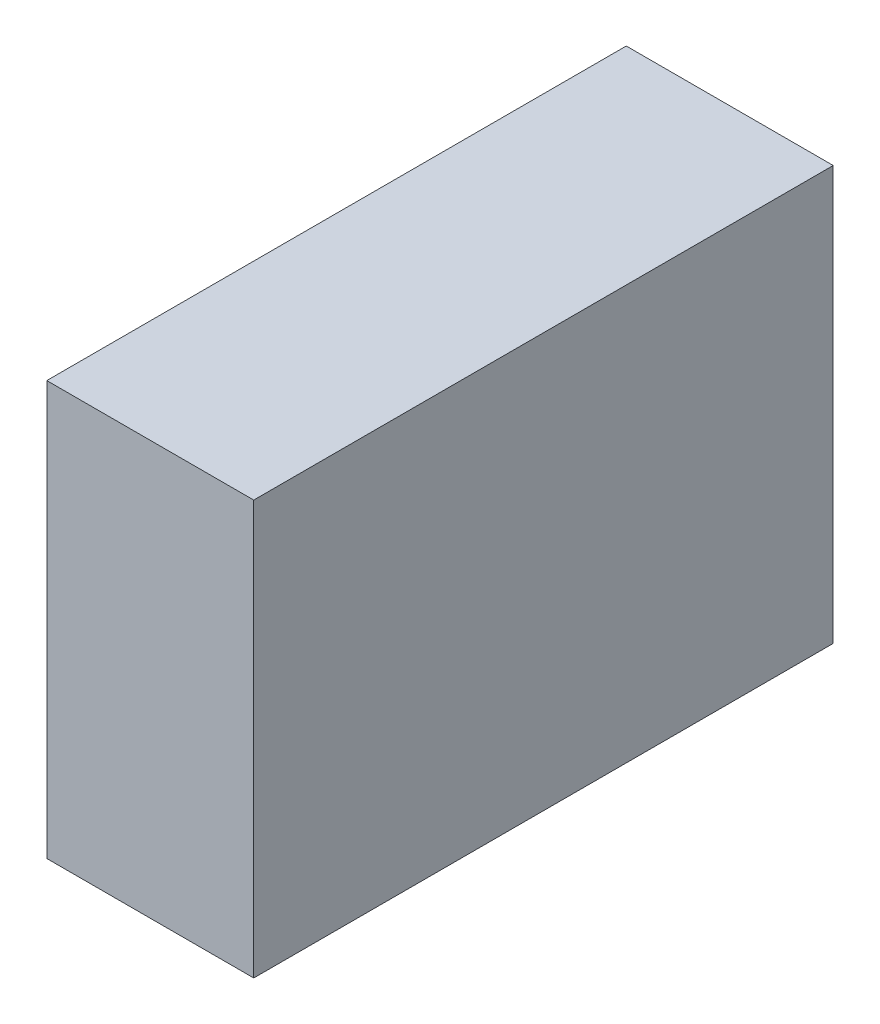
SolidWorks part; units mm, degrees
ref_plane "Ebene vorne" through (0, 0, 0) normal (0, 0, 1) x (1, 0, 0)
ref_plane "Ebene oben" through (0, 0, 0) normal (0, 1, 0) x (1, 0, 0)
ref_plane "Ebene rechts" through (0, 0, 0) normal (1, 0, 0) x (0, 0, -1)
sketch "Skizze1" plane through (0, 0, 0) normal (0, 0, 1) x (1, 0, 0)
  line L1 (5.452, 106.2874) -> (55.452, 106.2874)
  line L2 (5.452, 106.2874) -> (5.452, 6.2874)
  line L3 (5.452, 6.2874) -> (55.452, 6.2874)
  line L4 (55.452, 106.2874) -> (55.452, 6.2874)
  point P4 (0, 0)
  point P5 (0, 0)
  dimension "D1" = 50
  dimension "D2" = 100
other "AusrichtungGruppe1"
extrude "Aufsatz-Linear austragen1" add sketch "Skizze1" along normal blind 140
